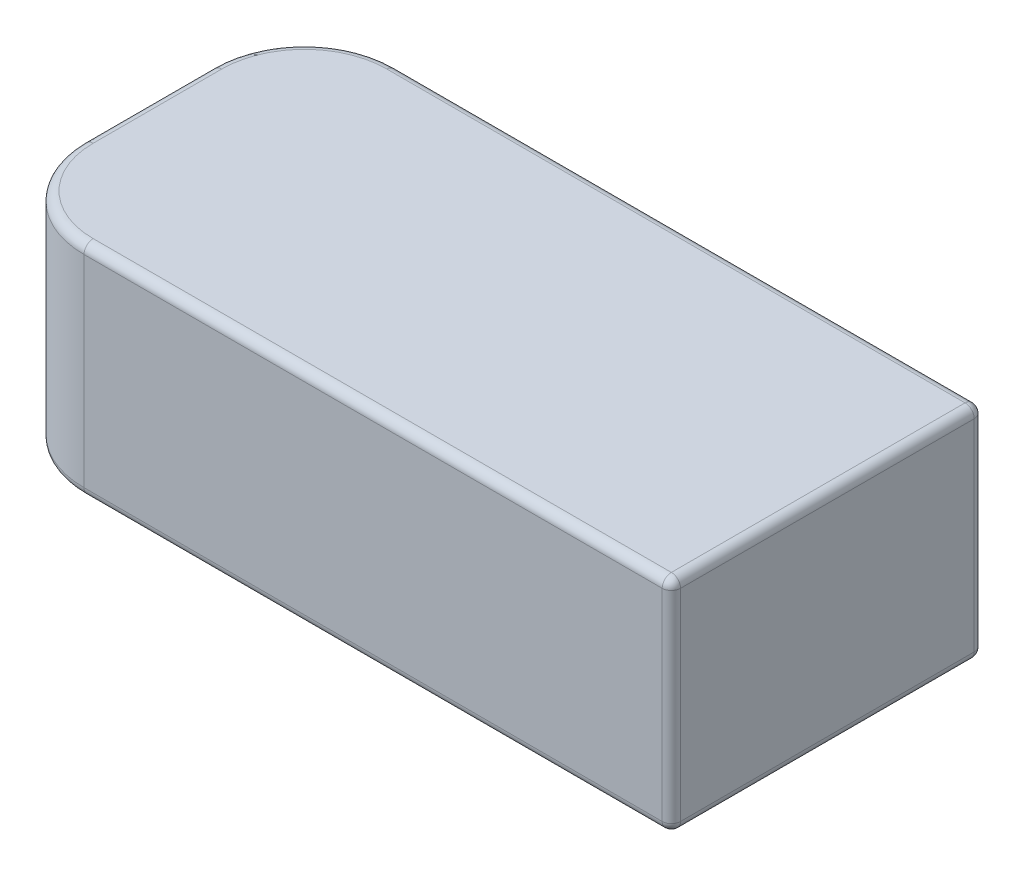
SolidWorks part; units mm, degrees
ref_plane "Front Plane" through (0, 0, 0) normal (0, 0, 1) x (1, 0, 0)
ref_plane "Top Plane" through (0, 0, 0) normal (0, 1, 0) x (1, 0, 0)
ref_plane "Right Plane" through (0, 0, 0) normal (1, 0, 0) x (0, 0, -1)
sketch "Sketch1" plane through (0, 0, 0) normal (0, 1, 0) x (1, 0, 0)
  line L1 (-37, -17) -> (37, -17)
  line L2 (-37, -17) -> (-37, 17)
  line L3 (-37, 17) -> (37, 17)
  line L4 (37, -17) -> (37, 17)
  line L5 (-37, -17) -> (37, 17) construction
  line L6 (-37, 17) -> (37, -17) construction
  point P0 (0, 0)
  dimension "D1" = 74
  dimension "D2" = 34
extrude "Boss-Extrude1" add sketch "Sketch1" along normal blind 24
fillet "Fillet1" radius 10 2 edges at (-37, 12, -17) (-37, 12, 17)
fillet "Fillet2" radius 1 14 edges at (-34.0711, 0, 14.0711) (5, 0, 17) (37, 0, 0) (5, 0, -17) (-34.0711, 0, -14.0711) (-37, 0, 0) (37, 24, 0) (5, 24, 17) (-34.0711, 24, 14.0711) (-37, 24, 0) (-34.0711, 24, -14.0711) (5, 24, -17) (37, 12, 17) (37, 12, -17)
